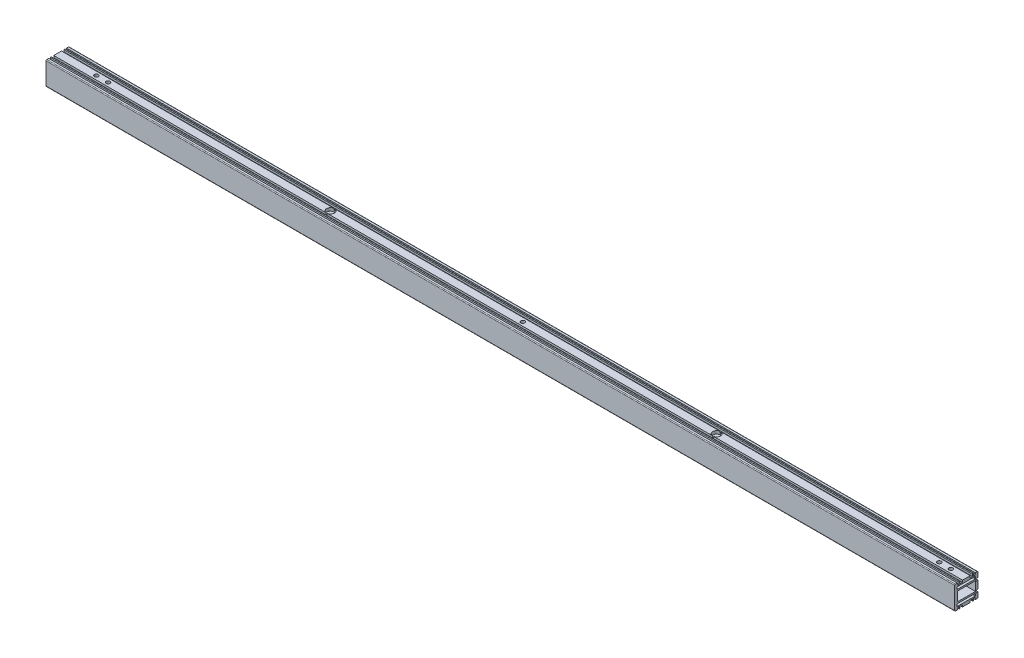
SolidWorks part; units mm, degrees
ref_plane "前视基准面" through (0, 0, 0) normal (0, 0, 1) x (1, 0, 0)
ref_plane "上视基准面" through (0, 0, 0) normal (0, 1, 0) x (1, 0, 0)
ref_plane "右视基准面" through (0, 0, 0) normal (1, 0, 0) x (0, 0, -1)
sketch "草图1" plane through (0, 0, 0) normal (1, 0, 0) x (0, 0, -1)
  line L0 (-15, 15) -> (15, -15) construction
  line L1 (-14, 15) -> (-11.5, 15)
  line L2 (-15, 14) -> (-15, -14)
  line L3 (-14, -15) -> (-11.5, -15)
  line L4 (15, 14) -> (15, 8)
  line L5 (15, 15) -> (-15, -15) construction
  line L6 (-11.5, 15) -> (-11.5, 13.5)
  line L7 (-11.5, 13.5) -> (-11.4, 13.5)
  line L8 (-11, 13.1) -> (-11, 12)
  line L9 (-11, 12) -> (-9.5, 12)
  line L10 (-9.5, 12) -> (-9.5, 15)
  line L11 (-9.5, 15) -> (-8, 15)
  line L12 (-8, 15) -> (-8, 12.5)
  line L13 (-8, 12.5) -> (-5, 12.5)
  line L14 (-5, 12.5) -> (-5, 15)
  line L15 (-5, 15) -> (5, 15)
  line L16 (0, 21.5201) -> (0, -18.309) construction
  line L17 (0, 55) -> (0, -55) construction
  line L18 (5, 12.5) -> (5, 15)
  line L19 (8, 12.5) -> (5, 12.5)
  line L20 (8, 15) -> (8, 12.5)
  line L21 (9.5, 15) -> (8, 15)
  line L22 (9.5, 12) -> (9.5, 15)
  line L23 (11, 12) -> (9.5, 12)
  line L24 (11, 13.1) -> (11, 12)
  line L25 (11.5, 13.5) -> (11.4, 13.5)
  line L26 (11.5, 15) -> (11.5, 13.5)
  line L27 (8, 15) -> (9.5, 15)
  line L28 (11.5, 15) -> (14, 15)
  line L29 (-19.8303, 0) -> (22.13, 0) construction
  line L30 (55, 0) -> (-55, 0) construction
  line L31 (8, -15) -> (9.5, -15)
  line L32 (11.5, -15) -> (11.5, -13.5)
  line L33 (11.5, -13.5) -> (11.4, -13.5)
  line L34 (11, -13.1) -> (11, -12)
  line L35 (11, -12) -> (9.5, -12)
  line L36 (9.5, -12) -> (9.5, -15)
  line L37 (9.5, -15) -> (8, -15)
  line L38 (8, -15) -> (8, -12.5)
  line L39 (8, -12.5) -> (5, -12.5)
  line L40 (5, -12.5) -> (5, -15)
  line L41 (-5, -15) -> (5, -15)
  line L42 (-5, -12.5) -> (-5, -15)
  line L43 (-8, -12.5) -> (-5, -12.5)
  line L44 (-8, -15) -> (-8, -12.5)
  line L45 (-9.5, -15) -> (-8, -15)
  line L46 (-9.5, -12) -> (-9.5, -15)
  line L47 (-11, -12) -> (-9.5, -12)
  line L48 (-11, -13.1) -> (-11, -12)
  line L49 (-11.5, -13.5) -> (-11.4, -13.5)
  line L50 (-11.5, -15) -> (-11.5, -13.5)
  line L51 (-9.5, -15) -> (-8, -15)
  line L52 (-5, -15) -> (5, -15)
  line L53 (8, -15) -> (9.5, -15)
  line L54 (11.5, -15) -> (14, -15)
  line L55 (15, 8) -> (12.5, 8)
  line L56 (12.5, 8) -> (12.5, 5)
  line L57 (12.5, 5) -> (15, 5)
  line L58 (12.5, -5) -> (15, -5)
  line L59 (12.5, -8) -> (12.5, -5)
  line L60 (15, -8) -> (12.5, -8)
  line L61 (15, 5) -> (15, -5)
  line L62 (15, -8) -> (15, -14)
  line L63 (12, -10.5) -> (12, -8.5)
  line L64 (-11.5, 11) -> (11.5, 11)
  line L65 (-12, 10.5) -> (-12, 8.5)
  line L66 (-11.5, 8) -> (11.5, 8)
  line L67 (12, 10.5) -> (12, 8.5)
  line L68 (-11.5, -8) -> (11.5, -8)
  line L69 (-12, -10.5) -> (-12, -8.5)
  line L70 (-11.5, -11) -> (11.5, -11)
  line L72 (-11.75, 6) -> (11.75, 6)
  line L73 (-11.75, 6) -> (-11.75, -6)
  line L74 (-11.75, -6) -> (11.75, -6)
  line L75 (11.75, 6) -> (11.75, -6)
  arc A0 (12, 8.5) -> (11.5, 8) centre (11.5, 8.5) cw
  arc A1 (11.5, 11) -> (12, 10.5) centre (11.5, 10.5) cw
  arc A2 (-11.5, 11) -> (-12, 10.5) centre (-11.5, 10.5) ccw
  arc A3 (-11.5, 8) -> (-12, 8.5) centre (-11.5, 8.5) cw
  arc A4 (-11, -13.1) -> (-11.4, -13.5) centre (-11.4, -13.1) cw
  arc A5 (11.4, -13.5) -> (11, -13.1) centre (11.4, -13.1) cw
  arc A6 (11.4, 13.5) -> (11, 13.1) centre (11.4, 13.1) ccw
  arc A7 (-11, 13.1) -> (-11.4, 13.5) centre (-11.4, 13.1) ccw
  arc A8 (-11.5, -8) -> (-12, -8.5) centre (-11.5, -8.5) ccw
  arc A9 (-11.5, -11) -> (-12, -10.5) centre (-11.5, -10.5) cw
  arc A10 (11.5, -11) -> (12, -10.5) centre (11.5, -10.5) ccw
  arc A11 (12, -8.5) -> (11.5, -8) centre (11.5, -8.5) ccw
  arc A12 (14, 15) -> (15, 14) centre (14, 14) cw
  arc A13 (14, -15) -> (15, -14) centre (14, -14) ccw
  arc A14 (-15, -14) -> (-14, -15) centre (-14, -14) ccw
  arc A15 (-15, 14) -> (-14, 15) centre (-14, 14) cw
  point P69 (12, 11)
  point P72 (-12, 11)
  point P77 (-11, -13.5)
  point P80 (11, -13.5)
  point P83 (11, 13.5)
  point P86 (-11, 13.5)
  point P99 (-12, -11)
  point P100 (12, -11)
  dimension "D17" = 0.5
  dimension "D18" = 0.4
  dimension "D21" = 1
  dimension "D1" = 3.5
  dimension "D2" = 1.5
  dimension "D3" = 0.5
  dimension "D4" = 1.5
  dimension "D5" = 3
  dimension "D6" = 30
  dimension "D7" = 30
  dimension "D8" = 1.5
  dimension "D9" = 2.5
  dimension "D10" = 3
  dimension "D11" = 2.5
  dimension "D12" = 7
  dimension "D13" = 3
  dimension "D14" = 4
  dimension "D15" = 3
  dimension "D16" = 24
  dimension "D19" = 23.5
  dimension "D20" = 12
extrude "凸台-拉伸1" add sketch "草图1" along normal mid plane 1172 contours A15 L2 A14 L3 L50 L49 A4 L48 L47 L46 L45 L44 L43 L42 L41 L40 L39 L38 L31 L36 L35 L34 A5 L33 L32 L54 A13 L62 L60 L59 L58 L61 L57 L56 L55 L4 A12 L28 L26 L25 A6 L24 L23 L22 L21 L20 L19 L18 L15 L14 L13
hole_wizard "M6 螺纹孔1" positions "草图3" profile "草图2" tap size "M6" standard "GB"
sketch "草图3" plane through (0, 15, 0) normal (0, 1, 0) x (-1, 0, 0)
  line L0 (-586, 5) -> (-586, -5) construction
  line L1 (-586, 15) -> (586, 15) construction
  line L2 (-586, -15) -> (586, -15) construction
  point P0 (-566, 0)
  point P1 (-551, 0)
  point P4 (521, 0)
  point P7 (536, 0)
  point P17 (-14, 0)
  dimension "D1" = 20
  dimension "D2" = 15
  dimension "D3" = 572
  dimension "D4" = 15
sketch "草图2" plane through (566, 15, 0) normal (1, 0, 0) x (0, 0, 1)
  line L0 (0, 0) -> (0, 16.5022)
  line L1 (0, 16.5022) -> (2.5, 15)
  line L2 (2.5, 15) -> (2.5, 0)
  line L5 (2.5, 0) -> (0, 0)
  line L10 (0, 16.5022) -> (-2.5, 15) construction
  line L11 (0, -6.35) -> (0, 107.95) construction
  dimension "螺纹孔钻头直径" = 5
  dimension "螺纹孔钻头深度" = 15
  dimension "导头角度" = 118
cosmetic thread "孔螺蚊线1" parameters "D1"=9, "D2"=6
cosmetic thread "孔螺蚊线2" parameters "D1"=9, "D2"=6
cosmetic thread "孔螺蚊线3" parameters "D1"=9, "D2"=6
cosmetic thread "孔螺蚊线4" parameters "D1"=9, "D2"=6
cosmetic thread "孔螺蚊线30" parameters "D1"=9, "D2"=6
hole_wizard "M6 螺纹孔2" positions "草图5" profile "草图4" tap size "M6" standard "GB"
sketch "草图5" plane through (0, 0, -15) normal (0, 0, -1) x (-1, 0, 0)
  line L0 (556, -5) -> (556, 5) construction
  line L1 (-586, -15) -> (586, -15) construction
  line L2 (586, 5) -> (586, -5) construction
  point P0 (536, 0)
  point P1 (521, 0)
  point P4 (-551, 0)
  point P7 (-566, 0)
  point P15 (448, 0)
  point P17 (361, 0)
  point P19 (344, 0)
  dimension "D1" = 20
  dimension "D2" = 15
  dimension "D3" = 138
  dimension "D4" = 104
  dimension "D5" = 225
sketch "草图4" plane through (-536, 0, -15) normal (1, 0, 0) x (0, 1, 0)
  line L0 (0, 0) -> (0, 16.5022)
  line L1 (0, 16.5022) -> (2.5, 15)
  line L2 (2.5, 15) -> (2.5, 0)
  line L5 (2.5, 0) -> (0, 0)
  line L10 (0, 16.5022) -> (-2.5, 15) construction
  line L11 (0, -6.35) -> (0, 107.95) construction
  dimension "螺纹孔钻头直径" = 5
  dimension "螺纹孔钻头深度" = 15
  dimension "导头角度" = 118
cosmetic thread "孔螺蚊线5" parameters "D1"=3.25, "D2"=6
cosmetic thread "孔螺蚊线6" parameters "D1"=3.25, "D2"=6
cosmetic thread "孔螺蚊线7" parameters "D1"=3.25, "D2"=6
cosmetic thread "孔螺蚊线8" parameters "D1"=3.25, "D2"=6
cosmetic thread "孔螺蚊线27" parameters "D1"=3.25, "D2"=6
cosmetic thread "孔螺蚊线28" parameters "D1"=3.25, "D2"=6
cosmetic thread "孔螺蚊线29" parameters "D1"=3.25, "D2"=6
hole_wizard "M6 螺纹孔3" positions "草图7" profile "草图6" tap size "M6" standard "GB"
sketch "草图7" plane through (0, -15, 0) normal (0, -1, 0) x (1, 0, 0)
  line L0 (-219, 5) -> (-219, -5) construction
  line L1 (586, 15) -> (-586, 15) construction
  point P0 (-199, 0)
  point P1 (-184, 0)
  point P4 (551, 0)
  point P7 (566, 0)
  dimension "D1" = 20
  dimension "D2" = 15
sketch "草图6" plane through (-199, -15, 0) normal (1, 0, 0) x (0, 0, -1)
  line L0 (0, 0) -> (0, 16.5022)
  line L1 (0, 16.5022) -> (2.5, 15)
  line L2 (2.5, 15) -> (2.5, 0)
  line L5 (2.5, 0) -> (0, 0)
  line L10 (0, 16.5022) -> (-2.5, 15) construction
  line L11 (0, -6.35) -> (0, 107.95) construction
  dimension "螺纹孔钻头直径" = 5
  dimension "螺纹孔钻头深度" = 15
  dimension "导头角度" = 118
cosmetic thread "孔螺蚊线9" parameters "D1"=9, "D2"=6
cosmetic thread "孔螺蚊线10" parameters "D1"=9, "D2"=6
cosmetic thread "孔螺蚊线11" parameters "D1"=9, "D2"=6
cosmetic thread "孔螺蚊线12" parameters "D1"=9, "D2"=6
sketch "草图8" plane through (0, 15, 0) normal (0, 1, 0) x (-1, 0, 0)
  line L0 (-586, -15) -> (586, -15) construction
  line L1 (586, 5) -> (586, -5) construction
  line L2 (-586, 5) -> (-586, -5) construction
  circle A0 centre (234, 0) radius 5.05
  circle A1 centre (-264, 0) radius 5.05
  dimension "D1" = 10.1
  dimension "D2" = 15
  dimension "D3" = 352
  dimension "D4" = 15
  dimension "D5" = 322
extrude "切除-拉伸1" cut sketch "草图8" against normal through all
hole_wizard "M4 螺纹孔1" positions "草图10" profile "草图9" tap size "M4" standard "GB"
sketch "草图10" plane through (0, -15, 0) normal (0, -1, 0) x (1, 0, 0)
  line L0 (-586, 5) -> (-586, -5) construction
  line L1 (586, 15) -> (-586, 15) construction
  point P0 (-137, 0)
  point P1 (23, 0)
  point P3 (183, 0)
  point P5 (343, 0)
  point P7 (503, 0)
  dimension "D1" = 449
  dimension "D2" = 15
  dimension "D3" = 160
  dimension "D4" = 160
  dimension "D5" = 160
  dimension "D6" = 160
sketch "草图9" plane through (-137, -15, 0) normal (1, 0, 0) x (0, 0, -1)
  line L0 (0, 0) -> (0, 11.0914)
  line L1 (0, 11.0914) -> (1.65, 10.1)
  line L2 (1.65, 10.1) -> (1.65, 0)
  line L5 (1.65, 0) -> (0, 0)
  line L10 (0, 11.0914) -> (-1.65, 10.1) construction
  line L11 (0, -6.35) -> (0, 107.95) construction
  dimension "螺纹孔钻头直径" = 3.3
  dimension "螺纹孔钻头深度" = 10.1
  dimension "导头角度" = 118
cosmetic thread "孔螺蚊线13" parameters "D1"=8, "D2"=4
cosmetic thread "孔螺蚊线14" parameters "D1"=8, "D2"=4
cosmetic thread "孔螺蚊线15" parameters "D1"=8, "D2"=4
cosmetic thread "孔螺蚊线16" parameters "D1"=8, "D2"=4
cosmetic thread "孔螺蚊线17" parameters "D1"=8, "D2"=4
hole_wizard "M4 螺纹孔2" positions "草图12" profile "草图11" tap size "M4" standard "GB"
sketch "草图12" plane through (0, -15, 0) normal (0, -1, 0) x (1, 0, 0)
  line L0 (-586, 5) -> (-586, -5) construction
  line L1 (586, 15) -> (-586, 15) construction
  point P1 (-261, 0)
  point P3 (-461, 0)
  dimension "D1" = 125
  dimension "D2" = 15
  dimension "D3" = 200
  dimension "D4" = 15
sketch "草图11" plane through (-261, -15, 0) normal (1, 0, 0) x (0, 0, -1)
  line L0 (0, 0) -> (0, 11.0914)
  line L1 (0, 11.0914) -> (1.65, 10.1)
  line L2 (1.65, 10.1) -> (1.65, 0)
  line L5 (1.65, 0) -> (0, 0)
  line L10 (0, 11.0914) -> (-1.65, 10.1) construction
  line L11 (0, -6.35) -> (0, 107.95) construction
  dimension "螺纹孔钻头直径" = 3.3
  dimension "螺纹孔钻头深度" = 10.1
  dimension "导头角度" = 118
cosmetic thread "孔螺蚊线18" parameters "D1"=8, "D2"=4
cosmetic thread "孔螺蚊线19" parameters "D1"=8, "D2"=4
hole_wizard "M4 螺纹孔3" positions "草图14" profile "草图13" tap size "M4" standard "GB"
sketch "草图14" plane through (0, -15, 0) normal (0, -1, 0) x (1, 0, 0)
  line L0 (-586, 5) -> (-586, -5) construction
  line L1 (586, 15) -> (-586, 15) construction
  point P1 (-571, 0)
  point P3 (-496, 0)
  dimension "D1" = 15
  dimension "D2" = 75
  dimension "D3" = 15
  dimension "D4" = 15
sketch "草图13" plane through (-571, -15, 0) normal (1, 0, 0) x (0, 0, -1)
  line L0 (0, 0) -> (0, 11.0914)
  line L1 (0, 11.0914) -> (1.65, 10.1)
  line L2 (1.65, 10.1) -> (1.65, 0)
  line L5 (1.65, 0) -> (0, 0)
  line L10 (0, 11.0914) -> (-1.65, 10.1) construction
  line L11 (0, -6.35) -> (0, 107.95) construction
  dimension "螺纹孔钻头直径" = 3.3
  dimension "螺纹孔钻头深度" = 10.1
  dimension "导头角度" = 118
cosmetic thread "孔螺蚊线21" parameters "D1"=8, "D2"=4
cosmetic thread "孔螺蚊线22" parameters "D1"=8, "D2"=4
hole_wizard "M6 螺纹孔4" positions "草图16" profile "草图15" tap size "M6" standard "GB"
sketch "草图16" plane through (0, 0, -15) normal (0, 0, -1) x (-1, 0, 0)
  line L0 (586, 5) -> (586, -5) construction
  line L1 (234.7089, 15) -> (586, 15) construction
  line L3 (-586, 14) -> (-586, 8) construction
  point P0 (326, 0)
  point P1 (266, 0)
  point P3 (-296, 0)
  point P5 (-356, 0)
  dimension "D1" = 260
  dimension "D2" = 60
  dimension "D3" = 15
  dimension "D4" = 60
  dimension "D5" = 230
sketch "草图15" plane through (-326, 0, -15) normal (1, 0, 0) x (0, 1, 0)
  line L0 (0, 0) -> (0, 16.5022)
  line L1 (0, 16.5022) -> (2.5, 15)
  line L2 (2.5, 15) -> (2.5, 0)
  line L5 (2.5, 0) -> (0, 0)
  line L10 (0, 16.5022) -> (-2.5, 15) construction
  line L11 (0, -6.35) -> (0, 107.95) construction
  dimension "螺纹孔钻头直径" = 5
  dimension "螺纹孔钻头深度" = 15
  dimension "导头角度" = 118
cosmetic thread "孔螺蚊线23" parameters "D1"=3.25, "D2"=6
cosmetic thread "孔螺蚊线24" parameters "D1"=3.25, "D2"=6
cosmetic thread "孔螺蚊线25" parameters "D1"=3.25, "D2"=6
cosmetic thread "孔螺蚊线26" parameters "D1"=3.25, "D2"=6
